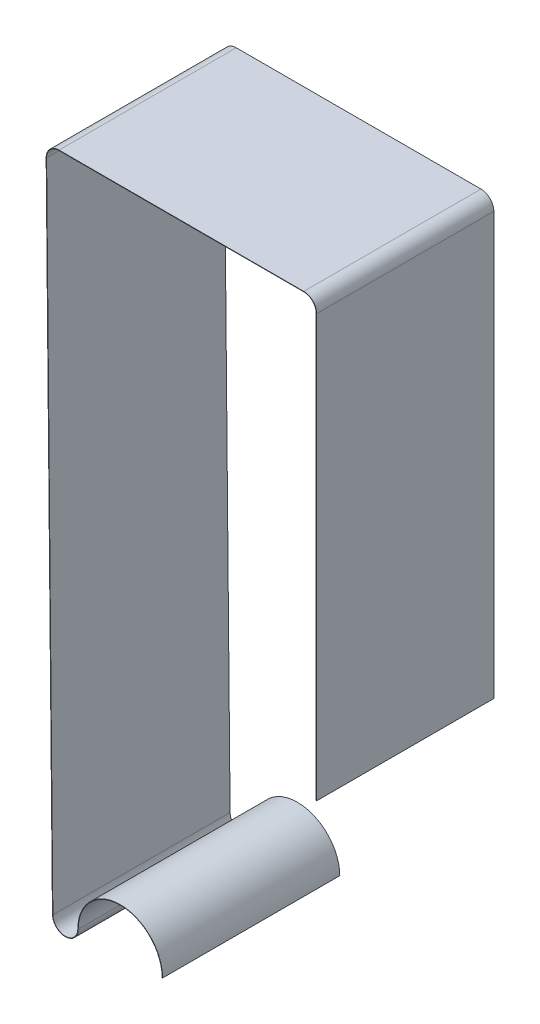
SolidWorks part; units mm, degrees
ref_plane "Front Plane" through (0, 0, 0) normal (0, 0, 1) x (1, 0, 0)
ref_plane "Top Plane" through (0, 0, 0) normal (0, 1, 0) x (1, 0, 0)
ref_plane "Right Plane" through (0, 0, 0) normal (1, 0, 0) x (0, 0, -1)
sketch "Sketch1" plane through (0, 0, 0) normal (0, 0, 1) x (1, 0, 0)
  line L0 (5, 1131.0731) -> (5, 1631.0731)
  line L2 (-10, 1646.0731) -> (-300, 1646.0731)
  line L3 (-314.9993, 1630.9284) -> (-307.5457, 857.8686)
  circle A0 centre (-10, 1631.0731) radius 15 construction
  arc A1 (5, 1631.0731) -> (-10, 1646.0731) centre (-10, 1631.0731) ccw
  circle A2 centre (-300, 1631.0731) radius 15 construction
  arc A3 (-300, 1646.0731) -> (-314.9993, 1630.9284) centre (-300, 1631.0731) ccw
  circle A4 centre (-292.5464, 858.0132) radius 15 construction
  arc A5 (-307.5457, 857.8686) -> (-277.5464, 858.0132) centre (-292.5464, 858.0132) ccw
  arc A6 (-277.5464, 858.0132) -> (-177.5464, 858.0132) centre (-227.5464, 858.0132) cw
  point P2 (0, 0)
  point P3 (0, 0)
  point P20 (0, 0)
  point P21 (5, 1134.3727)
  point P22 (-185.7921, 858.0132)
  point P23 (0, 0)
  point P24 (0, 0)
  dimension "D1" = 500
  dimension "D2" = 50
ref_plane "Plane1" through (0, 1131.0731, 0) normal (0, 1, 0) x (1, 0, 0)
sketch "Sketch2" plane through (0, 1131.0731, 0) normal (0, 1, 0) x (1, 0, 0)
  line L1 (4.75, -105) -> (5.25, -105)
  line L2 (4.75, -105) -> (4.75, 105)
  line L3 (4.75, 105) -> (5.25, 105)
  line L4 (5.25, -105) -> (5.25, 105)
  line L5 (4.75, -105) -> (5.25, 105) construction
  line L6 (4.75, 105) -> (5.25, -105) construction
  point P0 (5, 0)
  dimension "D1" = 0.5
  dimension "D2" = 210
sweep "Sweep1" add profiles "Sketch2" path "Sketch1"
